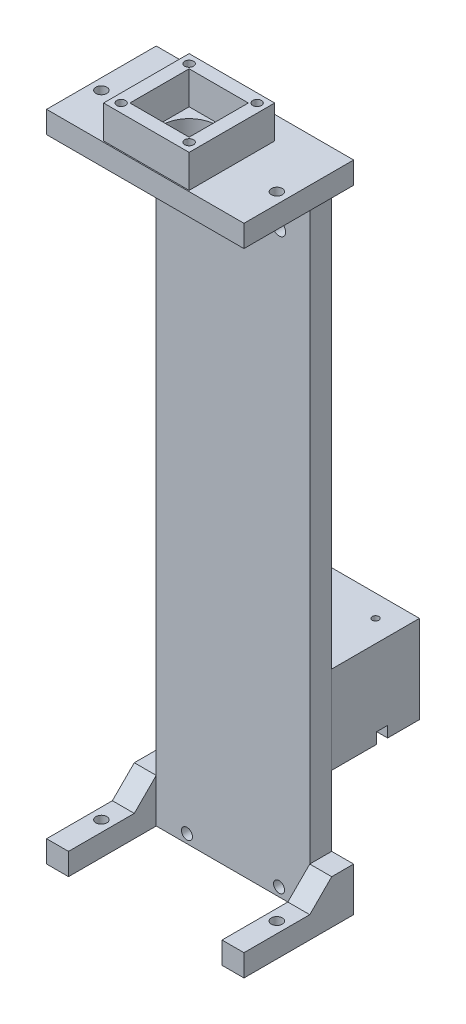
SolidWorks part; units mm, degrees
ref_plane "前视基准面" through (0, 0, 0) normal (0, 0, 1) x (1, 0, 0)
ref_plane "上视基准面" through (0, 0, 0) normal (0, 1, 0) x (1, 0, 0)
ref_plane "右视基准面" through (0, 0, 0) normal (1, 0, 0) x (0, 0, -1)
other "Configuration Table"
sketch "草图1" plane through (0, 0, 0) normal (0, 1, 0) x (1, 0, 0)
  line L1 (-32.1359, 17.2849) -> (37.8641, 17.2849)
  line L2 (-32.1359, 17.2849) -> (-32.1359, -22.7151)
  line L3 (-32.1359, -22.7151) -> (37.8641, -22.7151)
  line L4 (37.8641, 17.2849) -> (37.8641, -22.7151)
  dimension "D1" = 70
  dimension "D2" = 40
extrude "凸台-拉伸1" add sketch "草图1" along normal blind 40
sketch "草图2" plane through (0, 0, 0) normal (0, -1, 0) x (1, 0, 0)
  line L0 (-33.606, 17.7151) -> (40.5423, 17.7151) construction
  line L1 (-32.1359, 22.7151) -> (37.8641, 22.7151) construction
  line L2 (2.8641, 22.7151) -> (2.8641, -17.2849) construction
  line L3 (37.8641, -17.2849) -> (-32.1359, -17.2849) construction
  line L5 (-41.0082, -7.2849) -> (62.2571, -7.2849) construction
  circle A0 centre (-22.1359, 17.7151) radius 1.5
  circle A1 centre (27.8641, 17.7151) radius 1.5
  circle A2 centre (-22.1359, -7.2849) radius 1.5
  circle A3 centre (27.8641, -7.2849) radius 1.5
  dimension "D2" = 25
  dimension "D4" = 25
  dimension "D1" = 5
  dimension "D3" = 10
extrude "切除-拉伸1" cut sketch "草图2" against normal through all
sketch "草图4" plane through (0, 0, 0) normal (0, -1, 0) x (1, 0, 0)
  line L0 (-32.1359, 22.7151) -> (-32.1359, 32.7151)
  line L1 (-32.1359, 32.7151) -> (37.8641, 32.7151)
  line L2 (37.8641, 32.7151) -> (37.8641, 22.7151)
  line L3 (37.8641, 22.7151) -> (-32.1359, 22.7151)
  dimension "D1" = 10
extrude "凸台-拉伸2" add sketch "草图4" along normal blind 52 and the other way blind 236 separate body contours L3 L0 L1 L2
sketch "草图5" plane through (0, 0, 32.7151) normal (0, 0, 1) x (1, 0, 0)
  line L0 (-38.373, -48) -> (39.7493, -48) construction
  line L1 (-32.1359, -52) -> (37.8641, -52) construction
  line L2 (2.8641, 0) -> (2.8641, -52) construction
  line L3 (-32.1359, 0) -> (37.8641, 0) construction
  circle A0 centre (-18.1359, -48) radius 2.5
  circle A1 centre (23.8641, -48) radius 2.5
  dimension "D2" = 21
  dimension "D1" = 4
extrude "切除-拉伸2" cut sketch "草图5" against normal blind 10
sketch "草图6" plane through (0, 0, 32.7151) normal (0, 0, 1) x (1, 0, 0)
  line L0 (-39.8379, 212) -> (51.2489, 212) construction
  line L1 (-32.1359, 236) -> (37.8641, 236) construction
  line L2 (2.8641, 236) -> (2.8641, 203.179) construction
  circle A0 centre (-18.1359, 212) radius 3
  circle A1 centre (23.8641, 212) radius 3
  dimension "D2" = 21
  dimension "D1" = 24
extrude "切除-拉伸3" cut sketch "草图6" against normal blind 10
sketch "草图7" plane through (0, 0, 22.7151) normal (0, 0, -1) x (-1, 0, 0)
  line L0 (-37.8641, 236) -> (-37.8641, 246)
  line L1 (-37.8641, 246) -> (32.1359, 246)
  line L2 (32.1359, 246) -> (32.1359, 236)
  line L3 (32.1359, 236) -> (-37.8641, 236)
  dimension "D1" = 10
extrude "凸台-拉伸3" add sketch "草图7" against normal blind 50
sketch "草图8" plane through (0, 236, 0) normal (0, -1, 0) x (1, 0, 0)
  line L0 (-32.1359, 72.7151) -> (37.8641, 32.7151) construction
  line L1 (37.8641, 72.7151) -> (-32.1359, 32.7151) construction
  circle A0 centre (2.8641, 52.7151) radius 12.5
extrude "切除-拉伸4" cut sketch "草图8" against normal blind 10
sketch "草图12" plane through (0, 246, 0) normal (0, 1, 0) x (1, 0, 0)
  line L0 (2.8641, -52.7151) -> (49.57, -52.7151) construction
  line L1 (2.8641, -52.7151) -> (-42.4096, -52.7151) construction
  line L2 (2.8641, -22.7151) -> (2.8641, -78.6614) construction
  line L3 (-32.1359, -22.7151) -> (37.8641, -22.7151) construction
  line L4 (-14.6359, -35.2151) -> (-14.6359, -70.2151) construction
  line L5 (-16.6359, -33.2151) -> (22.3641, -33.2151)
  line L6 (-16.6359, -33.2151) -> (-16.6359, -72.2151)
  line L7 (-16.6359, -72.2151) -> (22.3641, -72.2151)
  line L8 (22.3641, -33.2151) -> (22.3641, -72.2151)
  line L9 (-14.6359, -70.2151) -> (20.3641, -70.2151) construction
  line L10 (20.3641, -35.2151) -> (20.3641, -70.2151) construction
  line L11 (-14.6359, -35.2151) -> (20.3641, -35.2151) construction
  dimension "D1" = 39
  dimension "D2" = 39
  dimension "D3" = 19.5
  dimension "D5" = 19.5
  dimension "D4" = 2
extrude "拉伸-薄壁2" add sketch "草图12" along normal blind 15 thin
sketch "草图14" plane through (0, 261, 0) normal (0, 1, 0) x (1, 0, 0)
  line L0 (-16.6359, -52.7151) -> (22.3641, -52.7151) construction
  line L1 (-16.6359, -33.2151) -> (-16.6359, -72.2151) construction
  line L2 (22.3641, -72.2151) -> (22.3641, -33.2151) construction
  line L3 (2.8641, -33.2151) -> (2.8641, -72.2151) construction
  line L4 (22.3641, -33.2151) -> (-16.6359, -33.2151) construction
  line L5 (-16.6359, -72.2151) -> (22.3641, -72.2151) construction
  circle A0 centre (-12.6359, -37.2151) radius 2
  circle A1 centre (18.3641, -37.2151) radius 2
  circle A2 centre (-12.6359, -68.2151) radius 2
  circle A3 centre (18.3641, -68.2151) radius 2
  dimension "D1" = 15.5
  dimension "D2" = 15.5
extrude "切除-拉伸5" cut sketch "草图14" against normal blind 25
sketch "草图15" plane through (0, 0, 0) normal (0, -1, 0) x (1, 0, 0)
  line L0 (-32.1359, -0.2849) -> (37.8641, -0.2849) construction
  line L1 (-32.1359, -17.2849) -> (-32.1359, 22.7151) construction
  line L2 (37.8641, 22.7151) -> (37.8641, -17.2849) construction
  line L3 (-32.1359, 2.2151) -> (37.8641, 2.2151)
  line L4 (37.8641, 2.2151) -> (37.8641, -2.7849)
  line L5 (37.8641, -2.7849) -> (-32.1359, -2.7849)
  line L6 (-32.1359, -2.7849) -> (-32.1359, 2.2151)
  circle A0 centre (-22.1359, -7.2849) radius 1.5 construction
  dimension "D1" = 7
  dimension "D2" = 5
  dimension "D3" = 2.5
extrude "切除-拉伸6" cut sketch "草图15" against normal blind 5
sketch "草图16" plane through (-32.1359, 0, 0) normal (-1, 0, 0) x (0, 0, 1)
  line L0 (22.7151, 246) -> (72.7151, 246)
  line L1 (72.7151, 246) -> (72.7151, 236)
  line L2 (72.7151, 236) -> (22.7151, 236)
  line L3 (22.7151, 246) -> (22.7151, -52) construction
  line L4 (22.7151, 236) -> (22.7151, 246)
extrude "凸台-拉伸5" add sketch "草图16" along normal blind 10
ref_plane "基准面3" through (0, 97, 0) normal (0, 1, 0) x (1, 0, 0)
mirror "镜向1" about plane through (0, 97, 0) normal (0, 1, 0) of "凸台-拉伸5"
ref_plane "基准面4" through (2.8641, 0, 0) normal (-1, 0, 0) x (0, 0, 1)
mirror "镜向2" about plane through (2.8641, 0, 0) normal (-1, 0, 0) of "镜向1", "凸台-拉伸5"
sketch "草图17" plane through (0, -52, 0) normal (0, -1, 0) x (1, 0, 0)
  line L0 (-32.1359, 52.7151) -> (37.8641, 52.7151) construction
  line L1 (-32.1359, 72.7151) -> (-32.1359, 32.7151) construction
  line L2 (37.8641, 72.7151) -> (37.8641, 32.7151) construction
  line L3 (2.8641, 72.7151) -> (2.8641, 32.7151) construction
  line L4 (47.8641, 72.7151) -> (-42.1359, 72.7151) construction
  line L5 (-32.1359, 32.7151) -> (37.8641, 32.7151) construction
  circle A0 centre (-37.1359, 52.7151) radius 2.5
  circle A1 centre (42.8641, 52.7151) radius 2.5
  dimension "D1" = 5
extrude "切除-拉伸7" cut sketch "草图17" against normal through all
sketch "草图18" plane through (0, -52, 0) normal (0, -1, 0) x (1, 0, 0)
  circle A0 centre (-37.1359, 52.7151) radius 2.5
  circle A1 centre (42.8641, 52.7151) radius 2.5
extrude "凸台-拉伸6" add sketch "草图18" against normal blind 5
sketch "草图21" plane through (0, 0, 22.7151) normal (0, 0, -1) x (-1, 0, 0)
  line L1 (-37.8641, 236) -> (-37.8641, -42) construction
  line L2 (-37.8641, -32) -> (-37.8641, -42)
  line L3 (-37.8641, -42) -> (-47.8641, -42)
  line L4 (-37.8641, -32) -> (-47.8641, -32)
  line L5 (-47.8641, -32) -> (-47.8641, -42)
  dimension "D1" = 10
extrude "凸台-拉伸8" add sketch "草图21" against normal up to surface (10 mm away) up to face at (-15.1359, 212, 32.7151)
mirror "镜向3" about plane through (2.8641, 0, 0) normal (-1, 0, 0) of "凸台-拉伸8"
sketch "草图22" plane through (47.8641, 0, 0) normal (1, 0, 0) x (0, 0, -1)
  line L0 (-32.7151, -32) -> (-42.7151, -42)
  line L1 (-32.7151, -42) -> (-72.7151, -42) construction
  line L2 (-42.7151, -42) -> (-32.7151, -42)
  line L3 (-32.7151, -42) -> (-32.7151, -32)
  dimension "D1" = 10
extrude "凸台-拉伸9" add sketch "草图22" against normal up to surface (10 mm away) up to face at (37.8641, 102, 27.7151)
sketch "草图23" plane through (-42.1359, 0, 0) normal (-1, 0, 0) x (0, 0, 1)
  line L0 (32.7151, -32) -> (42.7151, -42)
  line L1 (42.7151, -42) -> (32.7151, -42)
  line L2 (32.7151, -52) -> (32.7151, -32) construction
  line L3 (32.7151, -42) -> (32.7151, -32)
extrude "凸台-拉伸10" add sketch "草图23" against normal up to surface (10 mm away) contours L3 L0 L1 up to face at (-32.1359, -47, 52.7151)
sketch "草图25" plane through (-32.1359, 0, 0) normal (-1, 0, 0) x (0, 0, 1)
  line L0 (22.7151, 130) -> (27.7151, 130)
  line L1 (22.7151, 236) -> (22.7151, -32) construction
  line L2 (27.7151, 130) -> (27.7151, 90)
  line L3 (27.7151, 90) -> (32.7151, 90)
  line L4 (32.7151, 236) -> (32.7151, -32) construction
  line L5 (22.7151, 130) -> (22.7151, 40) construction
  dimension "D1" = 5
  dimension "D2" = 40
  dimension "D3" = 90
